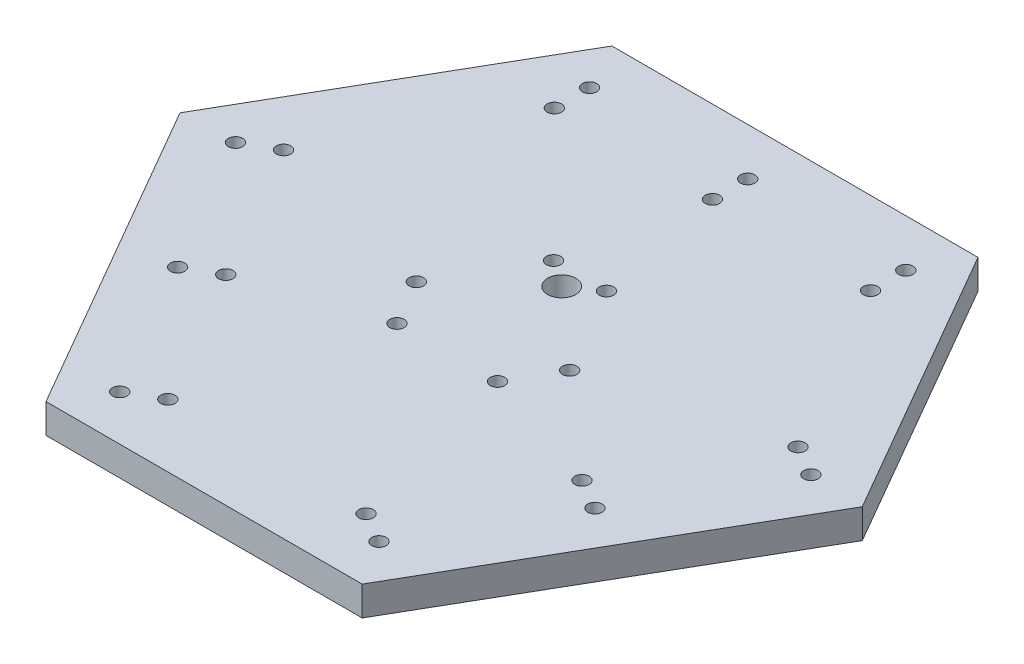
SolidWorks part; units mm, degrees
ref_plane "Front Plane" through (0, 0, 0) normal (0, 0, 1) x (1, 0, 0)
ref_plane "Top Plane" through (0, 0, 0) normal (0, 1, 0) x (1, 0, 0)
ref_plane "Right Plane" through (0, 0, 0) normal (1, 0, 0) x (0, 0, -1)
sketch "Sketch1" plane through (0, 0, 0) normal (0, 1, 0) x (1, 0, 0)
  line L1 (170, 98.1495) -> (-170, 98.1495)
  line L2 (-170, 98.1495) -> (0, -196.2991)
  line L3 (0, -196.2991) -> (170, 98.1495)
  circle A0 centre (0, 0) radius 98.1495 construction
  dimension "D1" = 340
extrude "Boss-Extrude1" add sketch "Sketch1" along normal blind 10
sketch "Sketch2" plane through (0, 10, 0) normal (0, 1, 0) x (1, 0, 0)
  line L1 (178.5, -103.057) -> (0, 206.114)
  line L2 (0, 206.114) -> (-178.5, -103.057)
  line L3 (-178.5, -103.057) -> (178.5, -103.057)
  circle A0 centre (0, 0) radius 103.057 construction
  dimension "D1" = 357
extrude "Cut-Extrude1" cut sketch "Sketch2" against normal blind 10 flip side to cut
sketch "Sketch3" plane through (0, 10, 0) normal (0, 1, 0) x (1, 0, 0)
  circle A0 centre (0, 18.7137) radius 4.8007
extrude "Cut-Extrude2" cut sketch "Sketch3" against normal blind 10
sketch "Sketch4" plane through (0, 10, 0) normal (0, 1, 0) x (1, 0, 0)
  line L0 (62.3333, 98.1495) -> (-62.3333, 98.1495) construction
  line L1 (0, 70.0495) -> (0, 82.0495) construction
  line L2 (0, 82.0495) -> (0, 98.1495) construction
  circle A0 centre (0, 82.0495) radius 2.45
  circle A1 centre (-53.8408, 82.0495) radius 2.45
  circle A2 centre (-53.8408, 70.0495) radius 2.45
  circle A3 centre (0, 70.0495) radius 2.45
  circle A4 centre (71.057, -41.0248) radius 2.45
  circle A5 centre (60.6647, -35.0248) radius 2.45
  circle A6 centre (-71.057, -41.0248) radius 2.45
  circle A7 centre (-60.6647, -35.0248) radius 2.45
  circle A8 centre (-87.5851, 11.6027) radius 2.45
  circle A9 centre (-97.9774, 5.6027) radius 2.45
  circle A10 centre (53.8408, 82.0495) radius 2.45
  circle A11 centre (53.8408, 70.0495) radius 2.45
  circle A12 centre (97.9774, 5.6027) radius 2.45
  circle A13 centre (87.5851, 11.6027) radius 2.45
  circle A14 centre (44.1366, -87.6523) radius 2.45
  circle A15 centre (33.7443, -81.6523) radius 2.45
  circle A16 centre (-33.7443, -81.6523) radius 2.45
  circle A17 centre (-44.1366, -87.6523) radius 2.45
  point P17 (0, 0)
  dimension "D1" = 4.9
  dimension "D3" = 4.9
  dimension "D6" = 4.9
  dimension "D7" = 4.9
  dimension "D8" = 4.9
  dimension "D9" = 4.9
  dimension "D10" = 4.9
  dimension "D11" = 4.9
  dimension "D12" = 4.9
  dimension "D13" = 4.9
  dimension "D14" = 4.9
  dimension "D15" = 4.9
  dimension "D16" = 4.9
  dimension "D17" = 4.9
  dimension "D2" = 16.1
  dimension "D4" = 12
  dimension "D5" = 3
extrude "Cut-Extrude3" cut sketch "Sketch4" against normal blind 10
sketch "Sketch5" plane through (0, 10, 0) normal (0, 1, 0) x (1, 0, 0)
  circle A0 centre (26.1069, -4.6805) radius 2.45
  circle A1 centre (17.1069, -20.269) radius 2.45
  circle A2 centre (-17.1069, -20.269) radius 2.45
  circle A3 centre (-26.1069, -4.6805) radius 2.45
  circle A4 centre (-9, 24.9495) radius 2.45
  circle A5 centre (9, 24.9495) radius 2.45
  dimension "D1" = 4.9
  dimension "D2" = 4.9
  dimension "D3" = 4.9
  dimension "D4" = 4.9
  dimension "D5" = 4.9
  dimension "D6" = 4.9
extrude "Cut-Extrude4" cut sketch "Sketch5" against normal blind 10
